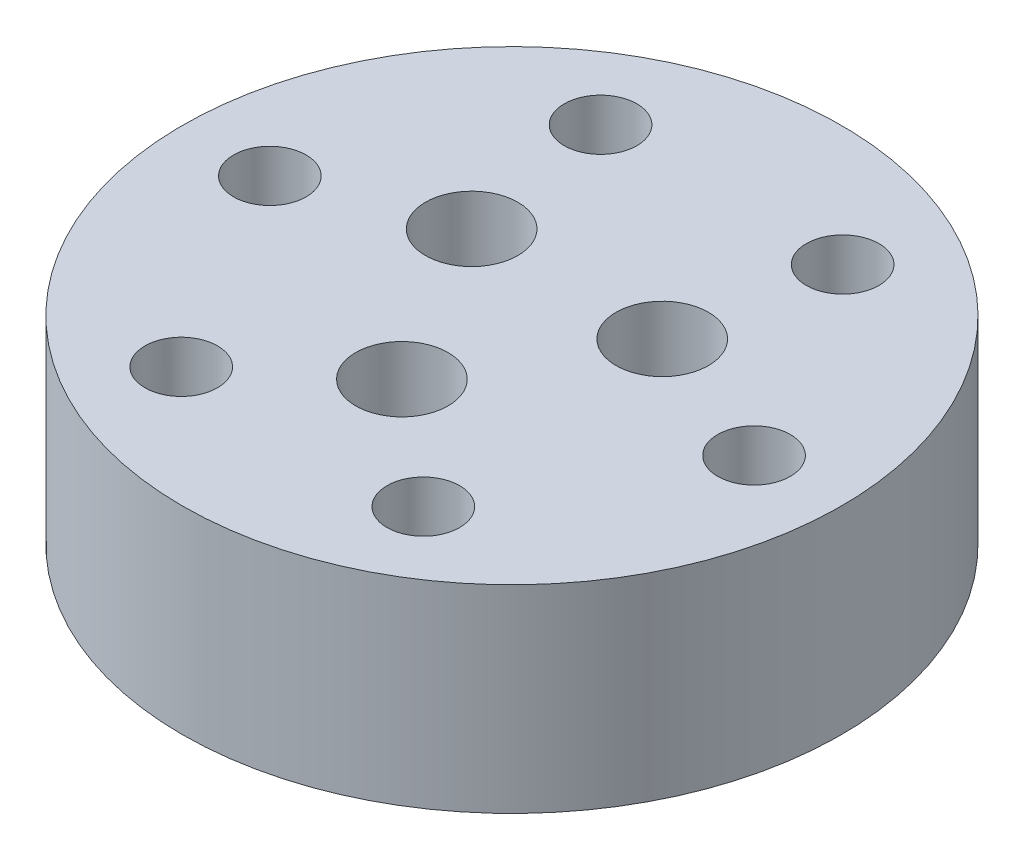
SolidWorks part; units mm, degrees
ref_plane "前视基准面" through (0, 0, 0) normal (0, 0, 1) x (1, 0, 0)
ref_plane "上视基准面" through (0, 0, 0) normal (0, 1, 0) x (1, 0, 0)
ref_plane "右视基准面" through (0, 0, 0) normal (1, 0, 0) x (0, 0, -1)
other "Configuration Table"
sketch "草图1" plane through (0, 0, 0) normal (0, 1, 0) x (1, 0, 0)
  circle A0 centre (0, 0) radius 14.975
  dimension "D1" = 29.95
extrude "凸台-拉伸1" add sketch "草图1" along normal blind 9
sketch "草图2" plane through (0, 0, 0) normal (0, -1, 0) x (1, 0, 0)
  circle A0 centre (0, 0) radius 11 construction
  circle A1 centre (-11, 0) radius 1.65
  circle A2 centre (-5.5, 9.5263) radius 1.65
  circle A3 centre (5.5, 9.5263) radius 1.65
  circle A4 centre (11, 0) radius 1.65
  circle A5 centre (5.5, -9.5263) radius 1.65
  circle A6 centre (-5.5, -9.5263) radius 1.65
  point P15 (0, 0)
  dimension "D1" = 22
  dimension "D2" = 3.3
  dimension "D3" = 6
extrude "切除-拉伸1" cut sketch "草图2" against normal blind 10
sketch "草图3" plane through (0, 0, 0) normal (0, -1, 0) x (1, 0, 0)
  circle A0 centre (0, 0) radius 5 construction
  circle A1 centre (0, 5) radius 2.1
  circle A2 centre (4.3301, -2.5) radius 2.1
  circle A3 centre (-4.3301, -2.5) radius 2.1
  point P11 (0, 0)
  dimension "D1" = 10
  dimension "D2" = 4.2
  dimension "D3" = 3
extrude "切除-拉伸2" cut sketch "草图3" against normal through all
sketch "草图4" plane through (0, 0, 0) normal (0, -1, 0) x (1, 0, 0)
  circle A0 centre (0, 5) radius 3.65
  circle A1 centre (-4.3301, -2.5) radius 3.65
  circle A2 centre (4.3301, -2.5) radius 3.65
  dimension "D1" = 7.3
extrude "切除-拉伸3" cut sketch "草图4" against normal blind 4
